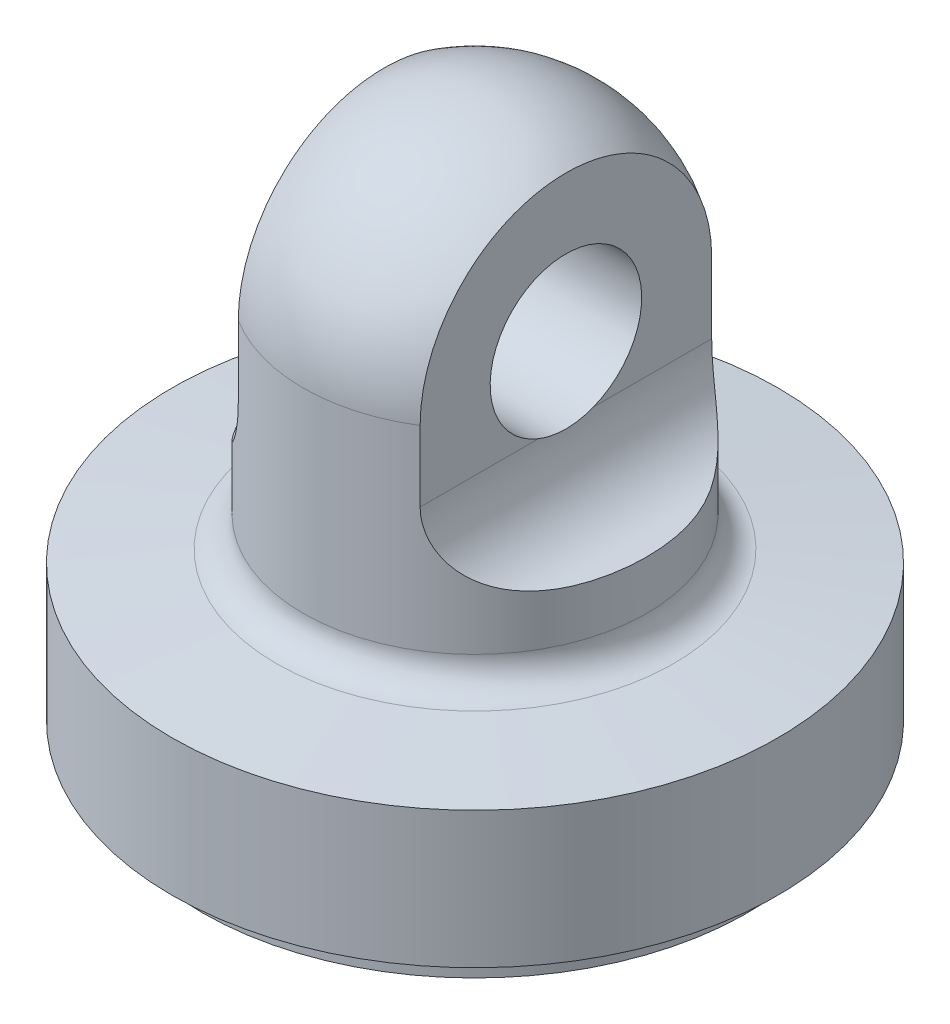
SolidWorks part; units mm, degrees
ref_plane "Front Plane" through (0, 0, 0) normal (0, 0, 1) x (1, 0, 0)
ref_plane "Top Plane" through (0, 0, 0) normal (0, 1, 0) x (1, 0, 0)
ref_plane "Right Plane" through (0, 0, 0) normal (1, 0, 0) x (0, 0, -1)
sketch "Sketch1" plane through (0, 0, 0) normal (0, 0, 1) x (1, 0, 0)
  line L0 (0, 0) -> (-12.7, 0) construction
  line L1 (-12.7, 0) -> (-12.7, 5.715)
  line L2 (-12.7, 5.715) -> (-8.3252, 6.2202)
  line L3 (-7.2009, 6.35) -> (0, 6.35) construction
  line L4 (0, 6.35) -> (0, 0)
  line L5 (0, 6.35) -> (0, 22.86)
  line L6 (-7.2009, 7.4818) -> (-7.2009, 15.6591)
  line L7 (-12.7, 0) -> (-11.43, 0)
  line L8 (-11.43, 0) -> (-11.43, -1.27)
  line L9 (-11.43, -1.27) -> (0, -1.27)
  line L10 (0, -1.27) -> (0, 0)
  arc A0 (-7.2009, 15.6591) -> (0, 22.86) centre (0, 15.6591) cw
  arc A1 (-7.2009, 7.4818) -> (-8.3252, 6.2202) centre (-8.4709, 7.4818) cw
  dimension "D6" = 1.27
  dimension "D1" = 6.35
  dimension "D2" = 5.715
  dimension "D3" = 7.2009
  dimension "D4" = 12.7
  dimension "D5" = 22.86
  dimension "D7" = 1.27
  dimension "D8" = 1.27
revolve "Revolve1" add sketch "Sketch1" angle 360 about L4
sketch "Sketch3" plane through (0, 0, 0) normal (0, 0, 1) x (1, 0, 0)
  line L0 (-3.81, 22.86) -> (-3.81, 12.7)
  line L1 (-3.81, 22.86) -> (-10.16, 22.86)
  line L2 (-10.16, 22.86) -> (-10.16, 12.7)
  line L3 (0, 0) -> (0, 22.86) construction
  line L4 (10.16, 22.86) -> (10.16, 12.7)
  line L5 (3.81, 22.86) -> (10.16, 22.86)
  line L6 (3.81, 22.86) -> (3.81, 12.7)
  arc A0 (-3.81, 12.7) -> (-10.16, 12.7) centre (-6.985, 12.7) cw
  arc A1 (7.2009, 15.6591) -> (-7.2009, 15.6591) centre (0, 15.6591) ccw construction
  arc A2 (3.81, 12.7) -> (10.16, 12.7) centre (6.985, 12.7) ccw
  point P4 (0, 0)
  point P12 (-10.4183, 12.1789)
  point P13 (0, 0)
  dimension "D1" = 3.81
  dimension "D2" = 6.35
  dimension "D3" = 10.16
extrude "Cut-Extrude1" cut sketch "Sketch3" against normal through all both and the other way through all contours A2 L4 L5 L6 | L2 A0 L0 L1
sketch "Sketch4" plane through (-3.81, 0, 0) normal (-1, 0, 0) x (0, 0, 1)
  circle A0 centre (0, 15.6591) radius 3.175
  arc A2 (6.1104, 15.6591) -> (-6.1104, 15.6591) centre (0, 15.6591) ccw construction
  point P2 (0, 0)
  point P3 (0, 0)
  point P7 (0, 0)
  point P8 (0, 0)
  dimension "D2" = 6.35
extrude "Cut-Extrude2" cut sketch "Sketch4" against normal through all both and the other way through all
